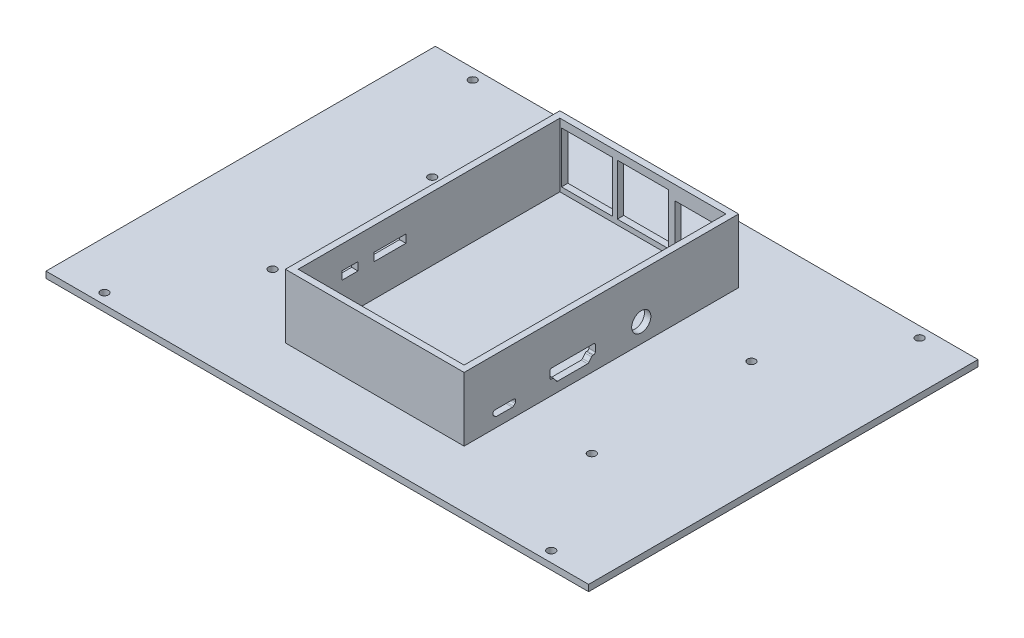
SolidWorks part; units mm, degrees
ref_plane "Plan de face" through (0, 0, 0) normal (0, 0, 1) x (1, 0, 0)
ref_plane "Plan de dessus" through (0, 0, 0) normal (0, 1, 0) x (1, 0, 0)
ref_plane "Plan de droite" through (0, 0, 0) normal (1, 0, 0) x (0, 0, -1)
sketch "Esquisse1" plane through (0, 0, 0) normal (0, 1, 0) x (1, 0, 0)
  line L0 (-85, -61) -> (85, 61) construction
  line L1 (-85, 61) -> (85, 61)
  line L2 (-85, 61) -> (-85, -61)
  line L3 (-85, -61) -> (85, -61)
  line L4 (85, 61) -> (85, -61)
  dimension "D1" = 170
  dimension "D2" = 122
extrude "Boss.-Extru.1" add sketch "Esquisse1" along normal blind 2
hole_wizard "Trou pour taraudage pour trou taraudé M3x0.51" positions "Esquisse2" profile "Esquisse3" hole size "M3x0.5" standard "Ansi Metric" end condition through all
sketch "Esquisse2" plane through (0, 2, 0) normal (0, 1, 0) x (1, 0, 0)
  line L0 (85, 61) -> (-85, -61) construction
  line L1 (-50, -25) -> (-85, -25) construction
  line L2 (-85, 61) -> (-85, -61) construction
  line L5 (50, 25) -> (85, 25) construction
  line L6 (85, -61) -> (85, 61) construction
  line L8 (51.0954, 25) -> (51.0954, 61) construction
  line L9 (85, 61) -> (-85, 61) construction
  line L11 (-50, -25) -> (-50, -61) construction
  line L12 (-85, -61) -> (85, -61) construction
  line L17 (70, 57.7) -> (70, 61) construction
  line L19 (-70, -61) -> (-70, -57.7) construction
  line L20 (70, 57.7) -> (85, 57.7) construction
  line L22 (-70, -57.7) -> (-85, -57.7) construction
  point P0 (-50, 25)
  point P2 (50, 25)
  point P4 (50, -25)
  point P6 (-50, -25)
  point P51 (70, 57.7)
  point P53 (-70, -57.7)
  point P55 (-70, 57.7)
  point P57 (70, -57.7)
  dimension "D1" = 100
  dimension "D2" = 50
  dimension "D3" = 3.3
  dimension "D4" = 15
sketch "Esquisse3" plane through (-50, 2, -25) normal (1, 0, 0) x (0, 0, 1)
  line L0 (0, 0) -> (0, 2)
  line L1 (0, 2) -> (1.25, 2)
  line L2 (1.25, 2) -> (1.25, 0)
  line L5 (1.25, 0) -> (0, 0)
  line L11 (0, -6.35) -> (0, 107.95) construction
  dimension "Diamètre du perçage jusqu'au prochain" = 2.5
  dimension "Profondeur du perçage jusqu'au prochain" = 2
sketch "Esquisse4" plane through (0, 2, 0) normal (0, -1, 0) x (1, 0, 0)
  line L0 (28, 43) -> (-28, -43) construction
  line L1 (28, -43) -> (-28, -43)
  line L2 (28, -43) -> (28, 43)
  line L3 (28, 43) -> (-28, 43)
  line L4 (-28, -43) -> (-28, 43)
  dimension "D1" = 56
  dimension "D2" = 86
extrude "Boss.-Extru.2" add sketch "Esquisse4" against normal blind 20
shell "Coque1" thickness 2
sketch "Esquisse5" plane through (28, 0, 0) normal (1, 0, 0) x (0, 0, -1)
  line L0 (-43, 6) -> (43, 6) construction
  line L1 (-43, 22) -> (-43, 2) construction
  line L2 (43, 22) -> (43, 2) construction
  line L3 (-33.4, 7) -> (-27.4, 7)
  line L4 (-26.9, 6.5) -> (-26.9, 5.9571)
  line L5 (-27.0464, 5.6036) -> (-27.5036, 5.1464)
  line L6 (-27.8571, 5) -> (-32.9429, 5)
  line L7 (-33.2964, 5.1464) -> (-33.7536, 5.6036)
  line L8 (-33.9, 5.9571) -> (-33.9, 6.5)
  line L10 (43, 2) -> (-43, 2) construction
  line L11 (-15.6, 9.5) -> (-2.4, 9.5)
  line L12 (-1.9, 9) -> (-1.9, 7)
  line L14 (-4.3034, 5) -> (-13.6966, 5)
  line L16 (-16.1, 7) -> (-16.1, 9)
  line L17 (-15.6, 6.5) -> (-15.3034, 6.5)
  line L18 (-14.9002, 6.2957) -> (-14.0998, 5.2043)
  line L19 (-3.9002, 5.2043) -> (-3.0998, 6.2957)
  line L20 (-2.6966, 6.5) -> (-2.4, 6.5)
  line L21 (-9, 9.5) -> (-9, 5) construction
  arc A0 (-27.4, 7) -> (-26.9, 6.5) centre (-27.4, 6.5) cw
  arc A1 (-33.9, 6.5) -> (-33.4, 7) centre (-33.4, 6.5) cw
  arc A2 (-26.9, 5.9571) -> (-27.0464, 5.6036) centre (-27.4, 5.9571) cw
  arc A3 (-27.5036, 5.1464) -> (-27.8571, 5) centre (-27.8571, 5.5) cw
  arc A4 (-32.9429, 5) -> (-33.2964, 5.1464) centre (-32.9429, 5.5) cw
  arc A5 (-33.7536, 5.6036) -> (-33.9, 5.9571) centre (-33.4, 5.9571) cw
  circle A6 centre (12.5, 8) radius 3
  arc A7 (-3.0998, 6.2957) -> (-2.6966, 6.5) centre (-2.6966, 6) cw
  arc A8 (-15.6, 6.5) -> (-16.1, 7) centre (-15.6, 7) cw
  arc A9 (-15.3034, 6.5) -> (-14.9002, 6.2957) centre (-15.3034, 6) cw
  arc A10 (-13.6966, 5) -> (-14.0998, 5.2043) centre (-13.6966, 5.5) cw
  arc A11 (-3.9002, 5.2043) -> (-4.3034, 5) centre (-4.3034, 5.5) cw
  arc A12 (-1.9, 7) -> (-2.4, 6.5) centre (-2.4, 7) cw
  arc A13 (-2.4, 9.5) -> (-1.9, 9) centre (-2.4, 9) cw
  arc A14 (-15.6, 9.5) -> (-16.1, 9) centre (-15.6, 9) ccw
  point P20 (-26.9, 7)
  point P23 (-33.9, 7)
  point P28 (-27.65, 5)
  point P31 (-33.15, 5)
  point P44 (-2.95, 6.5)
  point P47 (-16.1, 6.5)
  point P50 (-15.05, 6.5)
  point P53 (-13.95, 5)
  point P56 (-4.05, 5)
  point P61 (-1.9, 9.5)
  point P64 (-16.1, 9.5)
  point P70 (-30.4, 7)
  dimension "D6" = 0.5
  dimension "D7" = 0.5
  dimension "D15" = 6
  dimension "D16" = 2
  dimension "D17" = 0.5
  dimension "D2" = 7
  dimension "D3" = 2
  dimension "D4" = 5.5
  dimension "D5" = 4
  dimension "D8" = 14.2
  dimension "D9" = 4.5
  dimension "D10" = 9.9
  dimension "D11" = 3
  dimension "D12" = 12.1
  dimension "D13" = 1
  dimension "D14" = 1
  dimension "D18" = 12.6
  dimension "D19" = 34
  dimension "D20" = 55.5
extrude "Enlèv. mat.-Extru.1" cut sketch "Esquisse5" against normal up to next
sketch "Esquisse6" plane through (0, 0, -43) normal (0, 0, -1) x (-1, 0, 0)
  line L0 (26, 22) -> (26, 2) construction
  line L1 (9.5, 19.6) -> (25.5, 19.6)
  line L2 (9.5, 19.6) -> (9.5, 3.6)
  line L3 (9.5, 3.6) -> (25.5, 3.6)
  line L4 (25.5, 19.6) -> (25.5, 3.6)
  line L5 (-8, 19.6) -> (8, 19.6)
  line L6 (-8, 19.6) -> (-8, 3.6)
  line L7 (-8, 3.6) -> (8, 3.6)
  line L8 (8, 19.6) -> (8, 3.6)
  line L9 (-26, 17.6) -> (-10, 17.6)
  line L10 (-26, 17.6) -> (-26, 3.6)
  line L11 (-26, 3.6) -> (-10, 3.6)
  line L12 (-10, 17.6) -> (-10, 3.6)
  line L13 (28, 2) -> (-28, 2) construction
  dimension "D1" = 16
  dimension "D2" = 16
  dimension "D3" = 1.5
  dimension "D4" = 2
  dimension "D5" = 14
  dimension "D6" = 16
  dimension "D7" = 0.5
  dimension "D8" = 1.6
extrude "Enlèv. mat.-Extru.2" cut sketch "Esquisse6" against normal up to next
sketch "Esquisse7" plane through (-28, 0, 0) normal (-1, 0, 0) x (0, 0, 1)
  line L1 (7.2516, 14.6956) -> (17.2516, 14.6956)
  line L2 (7.2516, 14.6956) -> (7.2516, 12.1556)
  line L3 (7.2516, 12.1556) -> (17.2516, 12.1556)
  line L4 (17.2516, 14.6956) -> (17.2516, 12.1556)
  line L5 (22.2516, 14.6956) -> (27.2516, 14.6956)
  line L6 (22.2516, 14.6956) -> (22.2516, 12.1556)
  line L7 (22.2516, 12.1556) -> (27.2516, 12.1556)
  line L8 (27.2516, 14.6956) -> (27.2516, 12.1556)
  dimension "D1" = 10
  dimension "D2" = 5
  dimension "D3" = 5
  dimension "D4" = 2.54
extrude "Enlèv. mat.-Extru.3" cut sketch "Esquisse7" against normal up to next
